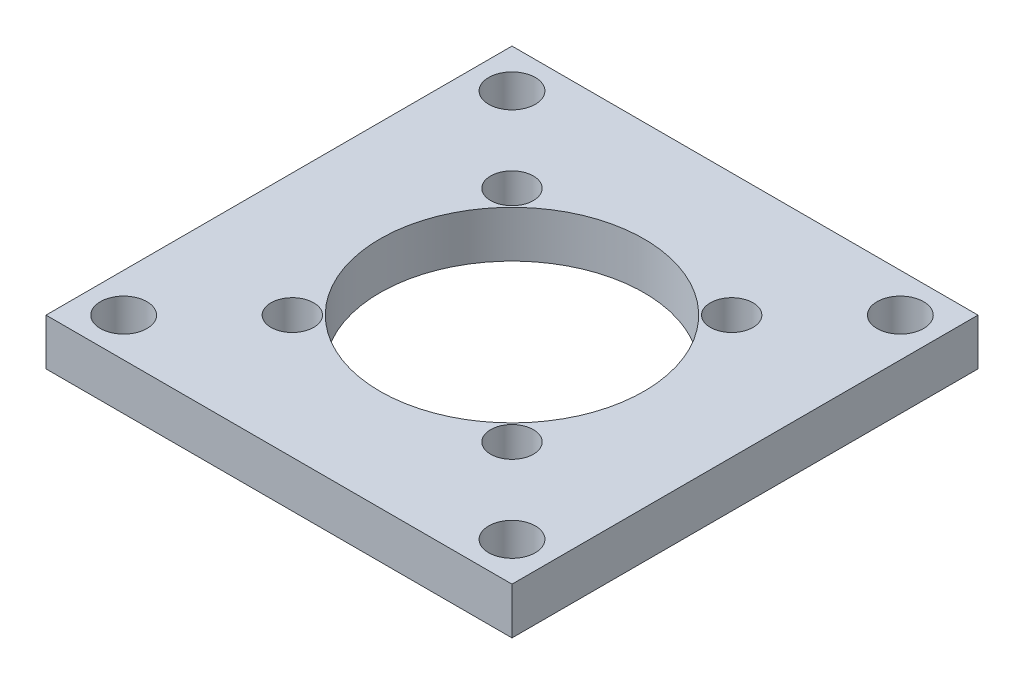
SolidWorks part; units mm, degrees
ref_plane "Front Plane" through (0, 0, 0) normal (0, 0, 1) x (1, 0, 0)
ref_plane "Top Plane" through (0, 0, 0) normal (0, 1, 0) x (1, 0, 0)
ref_plane "Right Plane" through (0, 0, 0) normal (1, 0, 0) x (0, 0, -1)
sketch "Sketch1" plane through (0, 0, 0) normal (0, 1, 0) x (1, 0, 0)
  line L0 (0, 60) -> (60, 0) construction
  line L1 (0, 0) -> (60, 0)
  line L2 (0, 0) -> (0, 60)
  line L3 (0, 60) -> (60, 60)
  line L4 (60, 0) -> (60, 60)
  circle A3 centre (15.8579, 44.1421) radius 2.75
  circle A4 centre (30, 30) radius 17
  circle A5 centre (30, 30) radius 20
  circle A6 centre (44.1421, 44.1421) radius 2.75
  circle A7 centre (44.1421, 15.8579) radius 2.75
  circle A8 centre (15.8579, 15.8579) radius 2.75
  point P19 (30, 30)
  dimension "D10" = 34
  dimension "D11" = 40
  dimension "D4" = 5.5
  dimension "D5" = 4
  dimension "D6" = 28.2843
  dimension "D8" = 60
  dimension "D9" = 60
  dimension "D2" = 30
  dimension "D3" = 30
extrude "Boss-Extrude1" add sketch "Sketch1" along normal blind 6 contours L0 L2 L1 A7 A5 A8 A3 | L3 L0 A3 A5 A6 A7 L4 | L0 A3 A5 A8 A7 A4 | A3 L0 A4 A7 A5 A6
sketch "Sketch3" plane through (0, 6, 0) normal (0, 1, 0) x (1, 0, 0)
  line L6 (0, 0) -> (0, 60) construction
  line L7 (0, 0) -> (60, 0) construction
  circle A1 centre (5, 55) radius 3
  circle A2 centre (55, 55) radius 3
  circle A3 centre (55, 5) radius 3
  circle A4 centre (5, 5) radius 3
  dimension "D1" = 5
  dimension "D2" = 5
  dimension "D5" = 6
  dimension "D6" = 6
  dimension "D7" = 6
  dimension "D8" = 6
  dimension "D3" = 50
  dimension "D4" = 50
extrude "Cut-Extrude1" cut sketch "Sketch3" against normal blind 10 contours A2 | A3 | A4 | A1
